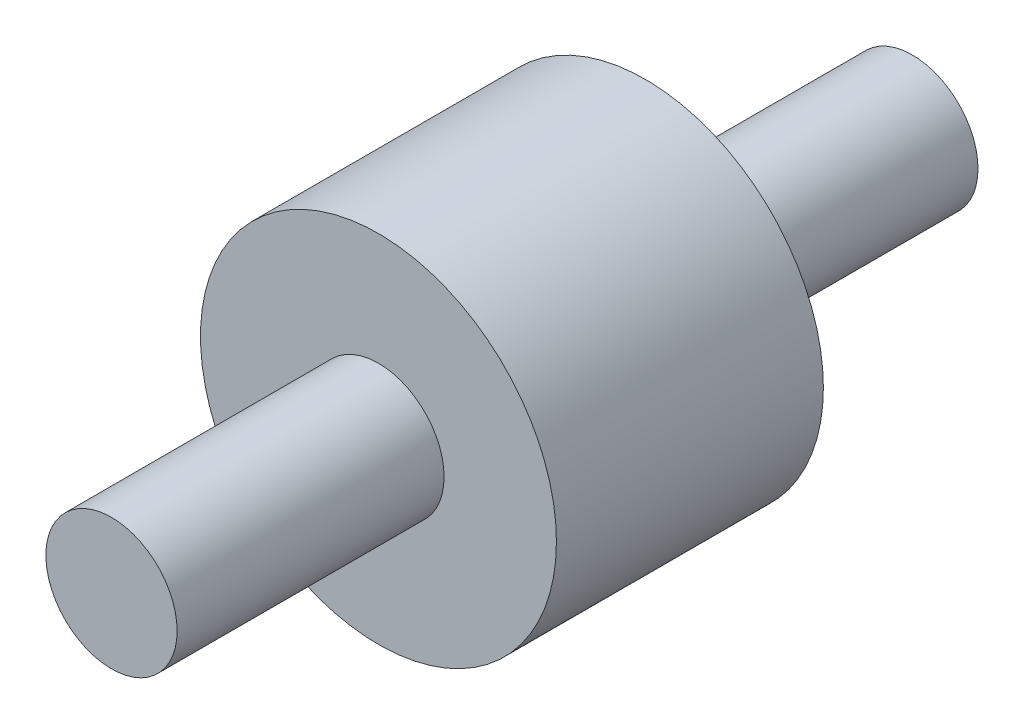
SolidWorks part; units mm, degrees
ref_plane "Alzado" through (0, 0, 0) normal (0, 0, 1) x (1, 0, 0)
ref_plane "Planta" through (0, 0, 0) normal (0, 1, 0) x (1, 0, 0)
ref_plane "Vista lateral" through (0, 0, 0) normal (1, 0, 0) x (0, 0, -1)
sketch "Croquis1" plane through (0, 0, 0) normal (0, 0, 1) x (1, 0, 0)
  circle A0 centre (0, 0) radius 8
  dimension "D1" = 16
extrude "Saliente-Extruir1" add sketch "Croquis1" along normal mid plane 12
sketch "Croquis2" plane through (0, 0, 6) normal (0, 0, 1) x (1, 0, 0)
  circle A0 centre (0, 0) radius 2.95
  dimension "D1" = 5.9
extrude "Saliente-Extruir2" add sketch "Croquis2" along normal blind 12
mirror "Simetría1" about plane through (0, 0, 0) normal (0, 0, 1) of "Saliente-Extruir2"
